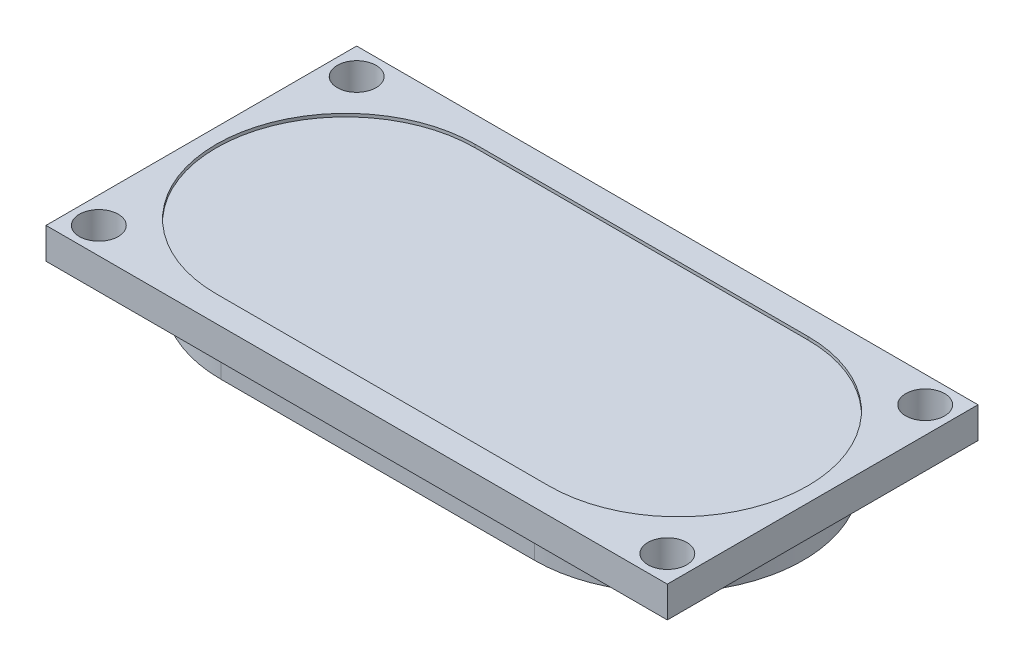
SolidWorks part; units mm, degrees
ref_plane "Front Plane" through (0, 0, 0) normal (0, 0, 1) x (1, 0, 0)
ref_plane "Top Plane" through (0, 0, 0) normal (0, 1, 0) x (1, 0, 0)
ref_plane "Right Plane" through (0, 0, 0) normal (1, 0, 0) x (0, 0, -1)
sketch "Sketch4" plane through (0, 0, 0) normal (0, 1, 0) x (1, 0, 0)
  line L1 (-20, -10) -> (20, -10)
  line L2 (-20, -10) -> (-20, 10)
  line L3 (-20, 10) -> (20, 10)
  line L4 (20, -10) -> (20, 10)
  line L5 (-20, -10) -> (20, 10) construction
  line L6 (-20, 10) -> (20, -10) construction
  point P0 (0, 0)
  dimension "D1" = 40
  dimension "D2" = 20
extrude "Boss-Extrude2" add sketch "Sketch4" along normal blind 2
sketch "Sketch5" plane through (0, 2, 0) normal (0, 1, 0) x (1, 0, 0)
  line L0 (-20, 10) -> (-20, -10) construction
  line L1 (20, 10) -> (-20, 10) construction
  line L2 (20, -10) -> (20, 10) construction
  line L3 (-20, -10) -> (20, -10) construction
  circle A0 centre (-18.3, 8.3) radius 1.25
  circle A1 centre (18.3, 8.3) radius 1.25
  circle A2 centre (-18.3, -8.3) radius 1.25
  circle A3 centre (18.3, -8.3) radius 1.25
  dimension "D1" = 2.5
  dimension "D5" = 2.5
  dimension "D6" = 2.5
  dimension "D8" = 2.5
  dimension "D2" = 1.7
  dimension "D3" = 1.7
  dimension "D4" = 1.7
  dimension "D7" = 1.7
extrude "Cut-Extrude1" cut sketch "Sketch5" against normal through all
sketch "Sketch6" plane through (0, 0, 0) normal (0, -1, 0) x (1, 0, 0)
  line L0 (-10.1, 0) -> (10.1, 0) construction
  line L1 (-10.1, 8.65) -> (10.1, 8.65)
  line L2 (-10.1, -8.65) -> (10.1, -8.65)
  arc A0 (-10.1, 8.65) -> (-10.1, -8.65) centre (-10.1, 0) ccw
  arc A1 (10.1, -8.65) -> (10.1, 8.65) centre (10.1, 0) ccw
  point P2 (0, 0)
  point P8 (-18.75, 0)
  point P9 (18.75, 0)
  dimension "D1" = 17.3
  dimension "D2" = 37.5
extrude "Boss-Extrude3" add sketch "Sketch6" along normal blind 2.3
sketch "Sketch7" plane through (0, -2.3, 0) normal (0, -1, 0) x (1, 0, 0)
  circle A0 centre (0, 0) radius 7.25
  dimension "D1" = 14.5
extrude "Boss-Extrude4" add sketch "Sketch7" along normal blind 1.2
sketch "Sketch8" plane through (0, 2, 0) normal (0, 1, 0) x (1, 0, 0)
  line L0 (-10.7066, 0) -> (10.7066, 0) construction
  line L1 (-10.7066, 8.3369) -> (10.7066, 8.3369)
  line L2 (-10.7066, -8.3369) -> (10.7066, -8.3369)
  arc A0 (-10.7066, 8.3369) -> (-10.7066, -8.3369) centre (-10.7066, 0) ccw
  arc A1 (10.7066, -8.3369) -> (10.7066, 8.3369) centre (10.7066, 0) ccw
  point P2 (0, 0)
extrude "Cut-Extrude2" cut sketch "Sketch8" against normal blind 0.2
